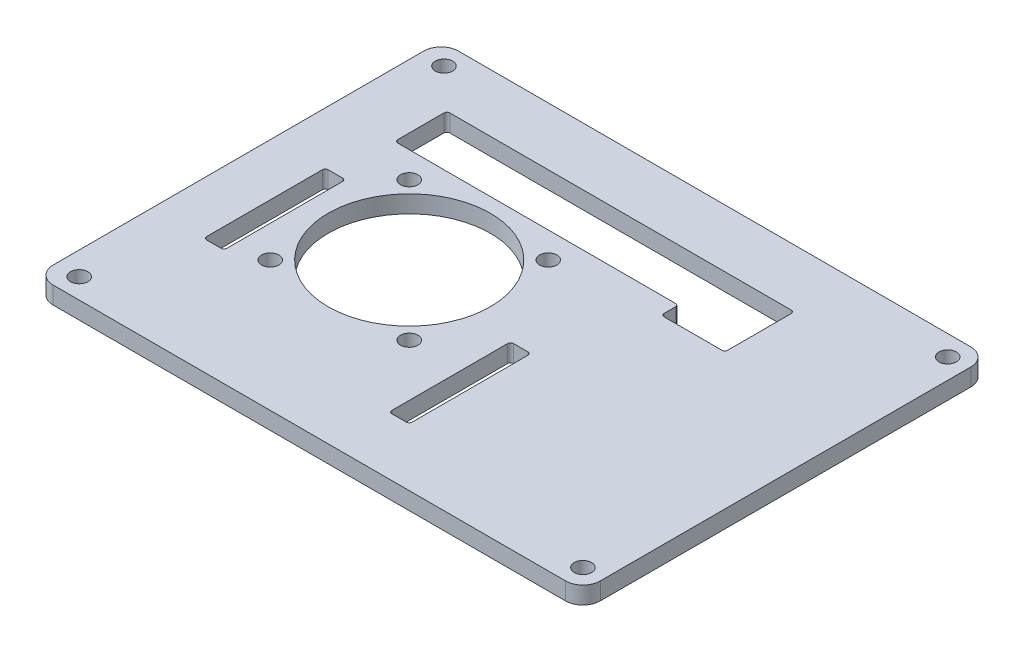
SolidWorks part; units mm, degrees
material "Acrylic (Medium-high impact)"
ref_plane "Front Plane" through (0, 0, 0) normal (0, 0, 1) x (1, 0, 0)
ref_plane "Top Plane" through (0, 0, 0) normal (0, 1, 0) x (1, 0, 0)
ref_plane "Right Plane" through (0, 0, 0) normal (1, 0, 0) x (0, 0, -1)
sketch "Sketch1" plane through (0, 0, 0) normal (0, 1, 0) x (1, 0, 0)
  line L1 (-47.25, 35) -> (47.25, 35)
  line L2 (-47.25, 35) -> (-47.25, -35)
  line L3 (-47.25, -35) -> (47.25, -35)
  line L4 (47.25, 35) -> (47.25, -35)
  line L5 (-47.25, 35) -> (47.25, -35) construction
  line L6 (-47.25, -35) -> (47.25, 35) construction
  point P0 (0, 0)
  dimension "D1" = 70
  dimension "D2" = 94.5
extrude "Boss-Extrude1" add sketch "Sketch1" along normal blind 3
sketch "Sketch2" plane through (0, 3, 0) normal (0, 1, 0) x (1, 0, 0)
  line L0 (-36.25, 25) -> (23.75, 25)
  line L1 (23.75, 25) -> (23.75, 13)
  line L2 (23.75, 13) -> (12.75, 13)
  line L3 (12.75, 13) -> (12.75, 16)
  line L4 (12.75, 16) -> (-36.25, 16)
  line L5 (-36.25, 16) -> (-36.25, 25)
  line L6 (-38.25, 6) -> (-38.25, -15)
  line L7 (-38.25, -15) -> (-34.75, -15)
  line L8 (-34.75, -15) -> (-34.75, 6)
  line L9 (-34.75, 6) -> (-38.25, 6)
  line L10 (3.75, -4) -> (7.25, -4)
  line L11 (7.25, -4) -> (7.25, -25)
  line L12 (7.25, -25) -> (3.75, -25)
  line L13 (3.75, -25) -> (3.75, -4)
  line L14 (-21.4584, 13.5) -> (-12.4944, 13.5) construction
  line L15 (-47.25, 35) -> (-47.25, -35) construction
  line L16 (47.25, 35) -> (-47.25, 35) construction
  line L18 (-32.25, -15.5) -> (-2.25, -15.5) construction
  line L19 (-47.25, -35) -> (47.25, -35) construction
  line L20 (-32.25, -15.5) -> (-32.25, 14.5) construction
  line L21 (-32.25, 14.5) -> (-2.25, 14.5) construction
  line L22 (-2.25, -15.5) -> (-2.25, 14.5) construction
  line L23 (-32.25, -15.5) -> (-2.25, 14.5) construction
  line L24 (-32.25, 14.5) -> (-2.25, -15.5) construction
  circle A0 centre (-17.25, -0.5) radius 14
  circle A1 centre (-5.25, 11.5) radius 1.5
  circle A2 centre (-29.25, 11.5) radius 1.5
  circle A3 centre (-29.25, -12.5) radius 1.5
  circle A4 centre (-5.25, -12.5) radius 1.5
  dimension "D11" = 28
  dimension "D12" = 3
  dimension "D4" = 11
  dimension "D5" = 10
  dimension "D6" = 12
  dimension "D7" = 9
  dimension "D8" = 11
  dimension "D9" = 60
  dimension "D10" = 30
  dimension "D3" = 3
  dimension "D13" = 10
  dimension "D14" = 3.5
  dimension "D15" = 9
  dimension "D16" = 21
  dimension "D17" = 19
  dimension "D18" = 24
  dimension "D19" = 10
  dimension "D20" = 40
  dimension "D21" = 21
  dimension "D22" = 3.5
  dimension "D23" = 30
  dimension "D24" = 3
  dimension "D25" = 2.5
  dimension "D1" = 2
  dimension "D2" = 2
extrude "Cut-Extrude1" cut sketch "Sketch2" against normal through all
fillet "Fillet1" radius 0.5 14 edges at (-34.75, 1.5, 15) (-38.25, 1.5, 15) (-38.25, 1.5, -6) (-34.75, 1.5, -6) (7.25, 1.5, 25) (3.75, 1.5, 25) (3.75, 1.5, 4) (7.25, 1.5, 4) (23.75, 1.5, -25) (23.75, 1.5, -13) (12.75, 1.5, -13) (12.75, 1.5, -16) (-36.25, 1.5, -16) (-36.25, 1.5, -25)
sketch "Sketch3" plane through (0, 3, 0) normal (0, 1, 0) x (1, 0, 0)
  line L0 (47.25, -35) -> (47.25, 35) construction
  line L2 (47.25, 35) -> (-47.25, 35) construction
  circle A0 centre (43.75, 31.5) radius 1.5
  circle A1 centre (-43.25, 31.5) radius 1.5
  circle A2 centre (-43.25, -31.5) radius 1.5
  circle A3 centre (43.75, -31.5) radius 1.5
  dimension "D1" = 3
  dimension "D2" = 3.5
  dimension "D3" = 3.5
  dimension "D4" = 2
  dimension "D5" = 87
  dimension "D6" = 63
  dimension "D7" = 2
extrude "Cut-Extrude2" cut sketch "Sketch3" against normal through all
fillet "Fillet2" radius 3 4 edges at (-47.25, 1.5, 35) (-47.25, 1.5, -35) (47.25, 1.5, -35) (47.25, 1.5, 35)
